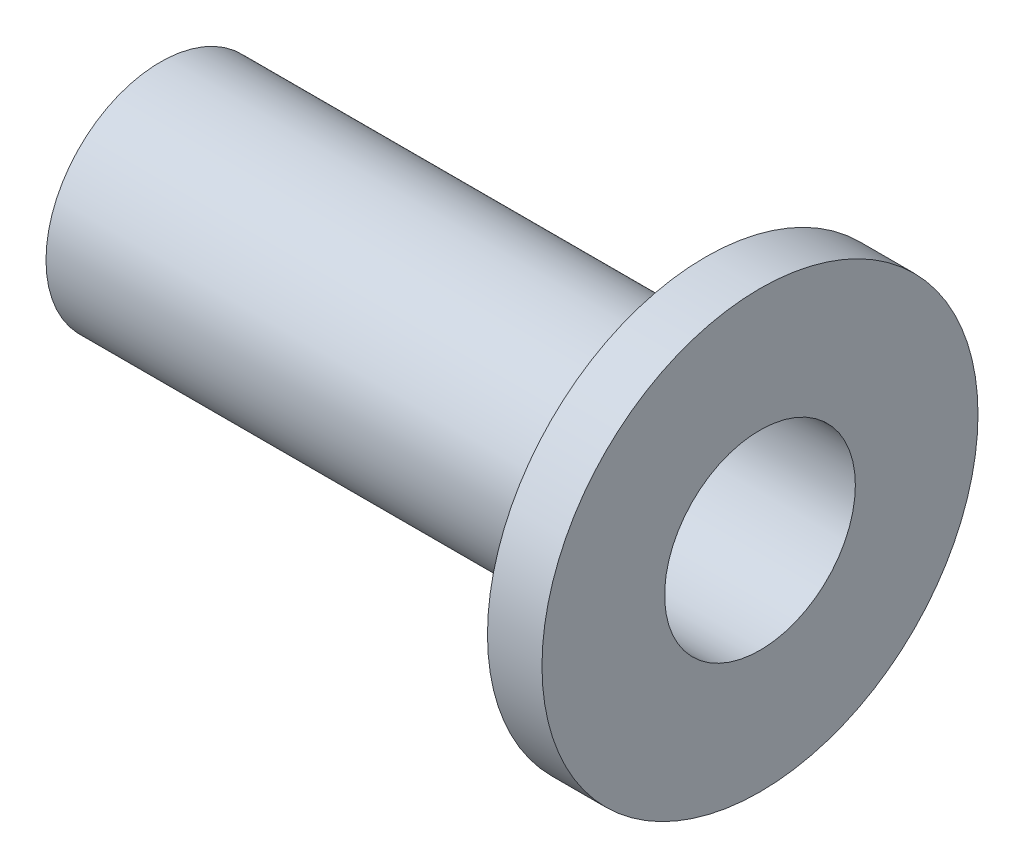
SolidWorks part; units mm, degrees
ref_plane "Front Plane" through (0, 0, 0) normal (0, 0, 1) x (1, 0, 0)
ref_plane "Top Plane" through (0, 0, 0) normal (0, 1, 0) x (1, 0, 0)
ref_plane "Right Plane" through (0, 0, 0) normal (1, 0, 0) x (0, 0, -1)
sketch "Sketch1" plane through (0, 0, 0) normal (0, 0, 1) x (1, 0, 0)
  line L0 (-106.4832, 24.957) -> (-96.4832, 24.957)
  line L1 (-96.4832, 24.957) -> (-96.4832, 26.857)
  line L2 (-96.4832, 26.857) -> (-95.4832, 26.857)
  line L3 (-95.4832, 26.857) -> (-95.4832, 24.607)
  line L4 (-106.4832, 24.957) -> (-106.4832, 24.607)
  line L5 (-106.4832, 24.607) -> (-95.4832, 24.607)
  line L6 (-95.4832, 22.857) -> (-106.4832, 22.857) construction
revolve "Revolve1" add sketch "Sketch1" angle 360 about L6
